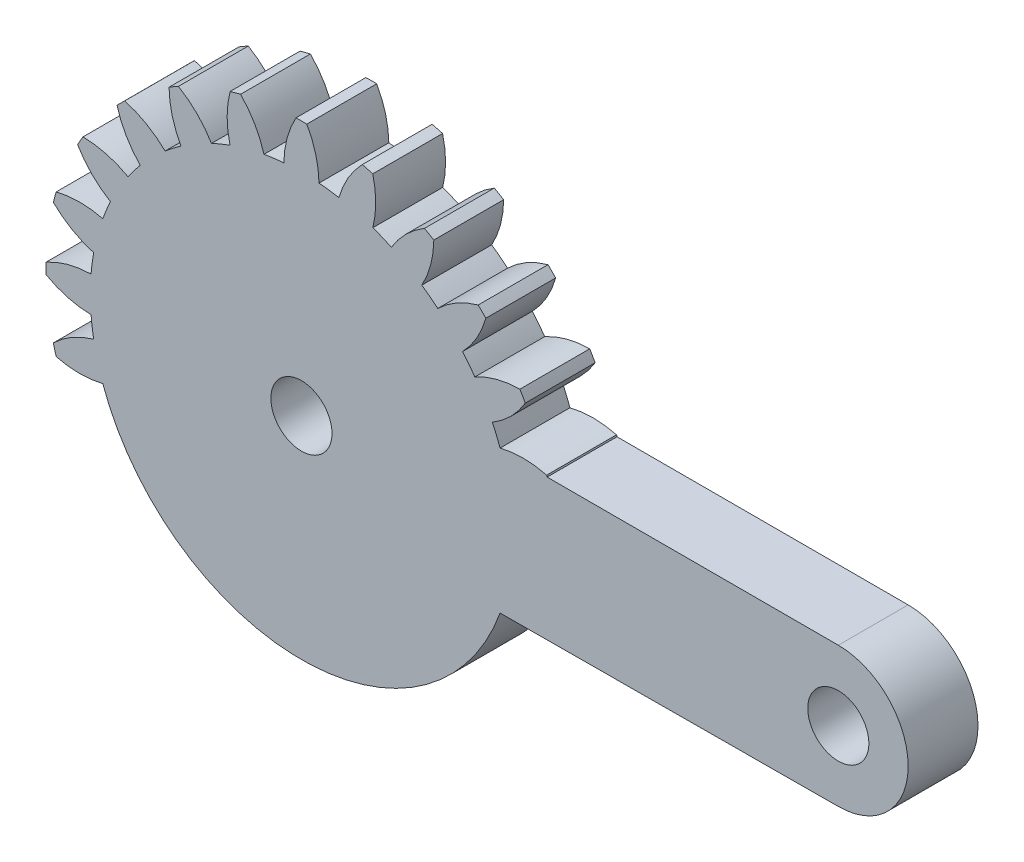
SolidWorks part; units mm, degrees
ref_plane "Front Plane" through (0, 0, 0) normal (0, 0, 1) x (1, 0, 0)
ref_plane "Top Plane" through (0, 0, 0) normal (0, 1, 0) x (1, 0, 0)
ref_plane "Right Plane" through (0, 0, 0) normal (1, 0, 0) x (0, 0, -1)
sketch "Sketch1" plane through (0, 0, 0) normal (0, 0, 1) x (1, 0, 0)
  line L0 (0, 0) -> (0, 14.63) construction
  line L1 (0, 0) -> (34.8406, 0) construction
  line L2 (11.4091, 4) -> (30.75, 4)
  line L3 (30.7686, -4) -> (11.3771, -4.0902)
  circle A0 centre (0, 0) radius 14.63
  circle A1 centre (0, 0) radius 12.09
  circle A2 centre (0, 0) radius 1.75
  arc A3 (0.31, 14.6267) -> (1.0062, 12.0481) centre (-4.3933, 11.9736) cw
  arc A4 (-0.31, 14.6267) -> (-1.0062, 12.0481) centre (4.3933, 11.9736) ccw
  arc A5 (4.0851, 14.0481) -> (4.0902, 11.3771) centre (-1.1446, 12.7027) cw
  arc A6 (3.4862, 14.2086) -> (2.1464, 11.898) centre (7.3426, 10.4285) ccw
  arc A7 (7.5818, 12.5121) -> (6.8954, 9.9308) centre (2.1821, 12.5661) cw
  arc A8 (7.0449, 12.8221) -> (5.1526, 10.937) centre (9.7915, 8.1728) ccw
  arc A9 (10.5619, 10.1234) -> (9.2308, 7.8078) centre (5.3601, 11.5731) cw
  arc A10 (10.1234, 10.5619) -> (7.8078, 9.2308) centre (11.5731, 5.3601) ccw
  arc A11 (12.8221, 7.0449) -> (10.937, 5.1526) centre (8.1728, 9.7915) cw
  arc A12 (12.5121, 7.5818) -> (9.9308, 6.8954) centre (12.5661, 2.1821) ccw
  arc A13 (14.2086, 3.4862) -> (11.898, 2.1464) centre (10.4285, 7.3426) cw
  arc A14 (14.0481, 4.0851) -> (11.3771, 4.0902) centre (12.7027, -1.1446) ccw
  arc A15 (14.6267, -0.31) -> (12.0481, -1.0062) centre (11.9736, 4.3933) cw
  arc A16 (14.6267, 0.31) -> (12.0481, 1.0062) centre (11.9736, -4.3933) ccw
  arc A17 (14.0481, -4.0851) -> (11.3771, -4.0902) centre (12.7027, 1.1446) cw
  arc A18 (14.2086, -3.4862) -> (11.898, -2.1464) centre (10.4285, -7.3426) ccw
  arc A19 (12.5121, -7.5818) -> (9.9308, -6.8954) centre (12.5661, -2.1821) cw
  arc A20 (12.8221, -7.0449) -> (10.937, -5.1526) centre (8.1728, -9.7915) ccw
  arc A21 (10.1234, -10.5619) -> (7.8078, -9.2308) centre (11.5731, -5.3601) cw
  arc A22 (10.5619, -10.1234) -> (9.2308, -7.8078) centre (5.3601, -11.5731) ccw
  arc A23 (7.0449, -12.8221) -> (5.1526, -10.937) centre (9.7915, -8.1728) cw
  arc A24 (7.5818, -12.5121) -> (6.8954, -9.9308) centre (2.1821, -12.5661) ccw
  arc A25 (3.4862, -14.2086) -> (2.1464, -11.898) centre (7.3426, -10.4285) cw
  arc A26 (4.0851, -14.0481) -> (4.0902, -11.3771) centre (-1.1446, -12.7027) ccw
  arc A27 (-0.31, -14.6267) -> (-1.0062, -12.0481) centre (4.3933, -11.9736) cw
  arc A28 (0.31, -14.6267) -> (1.0062, -12.0481) centre (-4.3933, -11.9736) ccw
  arc A29 (-4.0851, -14.0481) -> (-4.0902, -11.3771) centre (1.1446, -12.7027) cw
  arc A30 (-3.4862, -14.2086) -> (-2.1464, -11.898) centre (-7.3426, -10.4285) ccw
  arc A31 (-7.5818, -12.5121) -> (-6.8954, -9.9308) centre (-2.1821, -12.5661) cw
  arc A32 (-7.0449, -12.8221) -> (-5.1526, -10.937) centre (-9.7915, -8.1728) ccw
  arc A33 (-10.5619, -10.1234) -> (-9.2308, -7.8078) centre (-5.3601, -11.5731) cw
  arc A34 (-10.1234, -10.5619) -> (-7.8078, -9.2308) centre (-11.5731, -5.3601) ccw
  arc A35 (-12.8221, -7.0449) -> (-10.937, -5.1526) centre (-8.1728, -9.7915) cw
  arc A36 (-12.5121, -7.5818) -> (-9.9308, -6.8954) centre (-12.5661, -2.1821) ccw
  arc A37 (-14.2086, -3.4862) -> (-11.898, -2.1464) centre (-10.4285, -7.3426) cw
  arc A38 (-14.0481, -4.0851) -> (-11.3771, -4.0902) centre (-12.7027, 1.1446) ccw
  arc A39 (-14.6267, 0.31) -> (-12.0481, 1.0062) centre (-11.9736, -4.3933) cw
  arc A40 (-14.6267, -0.31) -> (-12.0481, -1.0062) centre (-11.9736, 4.3933) ccw
  arc A41 (-14.0481, 4.0851) -> (-11.3771, 4.0902) centre (-12.7027, -1.1446) cw
  arc A42 (-14.2086, 3.4862) -> (-11.898, 2.1464) centre (-10.4285, 7.3426) ccw
  arc A43 (-12.5121, 7.5818) -> (-9.9308, 6.8954) centre (-12.5661, 2.1821) cw
  arc A44 (-12.8221, 7.0449) -> (-10.937, 5.1526) centre (-8.1728, 9.7915) ccw
  arc A45 (-10.1234, 10.5619) -> (-7.8078, 9.2308) centre (-11.5731, 5.3601) cw
  arc A46 (-10.5619, 10.1234) -> (-9.2308, 7.8078) centre (-5.3601, 11.5731) ccw
  arc A47 (-7.0449, 12.8221) -> (-5.1526, 10.937) centre (-9.7915, 8.1728) cw
  arc A48 (-7.5818, 12.5121) -> (-6.8954, 9.9308) centre (-2.1821, 12.5661) ccw
  arc A49 (-3.4862, 14.2086) -> (-2.1464, 11.898) centre (-7.3426, 10.4285) cw
  arc A50 (-4.0851, 14.0481) -> (-4.0902, 11.3771) centre (1.1446, 12.7027) ccw
  arc A51 (30.75, 4) -> (30.7686, -4) centre (30.75, 0) cw
  circle A52 centre (30.75, 0) radius 1.75
  point P152 (0, 0)
  dimension "D1" = 3.5
  dimension "D2" = 24.18
  dimension "D3" = 29.26
  dimension "D6" = 5.4
  dimension "D9" = 4
  dimension "D10" = 3.5
  dimension "D4" = 0.62
  dimension "D8" = 30.75
  dimension "D11" = 1.15
  dimension "D7" = 24
extrude "Boss-Extrude2" add sketch "Sketch1" along normal blind 4 contours A51 L2 A0 L3 A52 | A0 A42 A1 A41 | A0 A44 A1 A43 | A0 A46 A1 A45 | A0 A48 A1 A47 | A0 A50 A1 A49 | A0 A4 A1 A3 | A0 A6 A1 A5 | A0 A8 A1 A7 | A0 A10 A1 A9 | A0 A12 A1 A11 | A13 A0 L2 A1 | A0 A16 A1 A15 | A0 A18 A1 L3 | A0 A14 A1 L2 | A16 A0 A13 A1 | A18 A0 A15 A1 | A0 A40 A1 A39 | A0 A38 A1 A37
sketch "Sketch2" plane through (0, 0, 4) normal (0, 0, 1) x (1, 0, 0)
  circle A0 centre (0, 0) radius 1.75 construction
  circle A1 centre (0, 0) radius 1.75
extrude "Cut-Extrude1" cut sketch "Sketch2" against normal through all
scale "Scale1" scale about centroid uniform scaling no x scale factor 1.5 y scale factor 1.5 z scale factor 1.5
